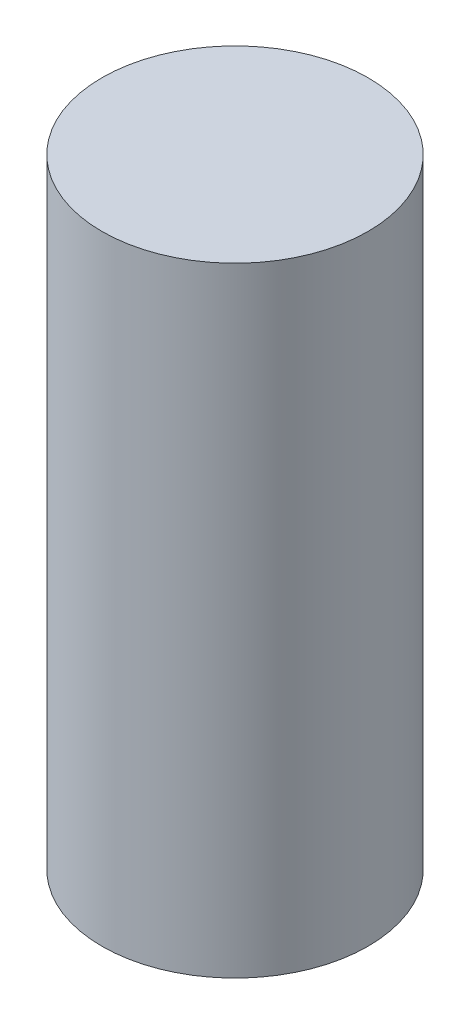
SolidWorks part; units mm, degrees
ref_plane "Front Plane" through (0, 0, 0) normal (0, 0, 1) x (1, 0, 0)
ref_plane "Top Plane" through (0, 0, 0) normal (0, 1, 0) x (1, 0, 0)
ref_plane "Right Plane" through (0, 0, 0) normal (1, 0, 0) x (0, 0, -1)
sketch "Sketch1" plane through (0, 0, 0) normal (0, 1, 0) x (1, 0, 0)
  circle A0 centre (0, 0) radius 21.5
  dimension "D1" = 43
extrude "Boss-Extrude1" add sketch "Sketch1" along normal blind 100
